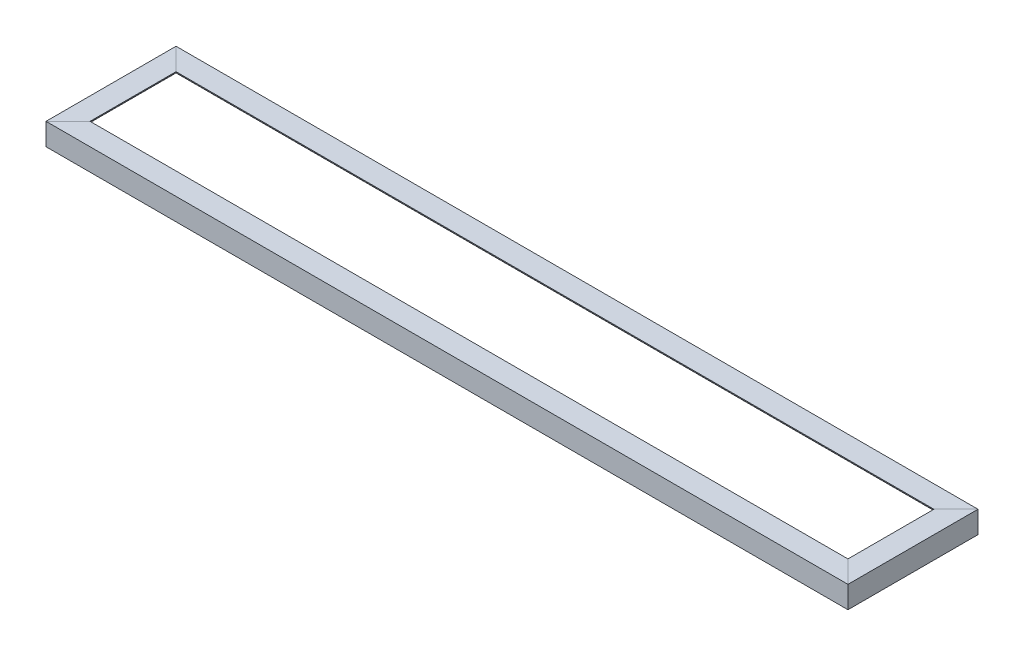
SolidWorks part; units mm, degrees
ref_plane "Alzado" through (0, 0, 0) normal (0, 0, 1) x (1, 0, 0)
ref_plane "Planta" through (0, 0, 0) normal (0, 1, 0) x (1, 0, 0)
ref_plane "Vista lateral" through (0, 0, 0) normal (1, 0, 0) x (0, 0, -1)
sketch "Croquis1" plane through (0, 0, 0) normal (0, 1, 0) x (1, 0, 0)
  line L1 (462.5, -75) -> (-462.5, -75)
  line L2 (462.5, -75) -> (462.5, 75)
  line L3 (462.5, 75) -> (-462.5, 75)
  line L4 (-462.5, -75) -> (-462.5, 75)
  line L5 (462.5, -75) -> (-462.5, 75) construction
  line L6 (462.5, 75) -> (-462.5, -75) construction
  point P0 (0, 0)
  dimension "D1" = 925
  dimension "D2" = 150
other "Hierro angular 1 X 1 X 0.125(1)"
ref_plane "Plano1" through (462.5, 0, 75) normal (-1, 0, 0) x (0, 0, -1)
sketch "Sketch11" plane through (462.5, 0, 75) normal (-1, 0, 0) x (0, 0, -1)
  line L0 (0, 0) -> (0, 25.4)
  line L1 (0, 25.4) -> (0.0051, 25.4)
  line L2 (3.175, 22.2301) -> (3.175, 7.9375)
  line L3 (7.9375, 3.175) -> (22.2301, 3.175)
  line L4 (25.4, 0.0051) -> (25.4, 0)
  line L5 (25.4, 0) -> (0, 0)
  arc A0 (25.4, 0.0051) -> (22.2301, 3.175) centre (22.2301, 0.0051) ccw
  arc A1 (0.0051, 25.4) -> (3.175, 22.2301) centre (0.0051, 22.2301) cw
  arc A2 (7.9375, 3.175) -> (3.175, 7.9375) centre (7.9375, 7.9375) cw
  point P10 (12.7, 0)
  point P14 (0, 12.7)
  point P15 (3.175, 12.7)
  point P16 (12.7, 3.175)
  point P17 (3.175, 25.4)
  point P18 (25.4, 3.175)
  point P19 (0, 0)
  dimension "D2" = 0.0051
  dimension "Radius_1" = 4.7625
  dimension "D1" = 3.175
  dimension "H_leg" = 25.4
